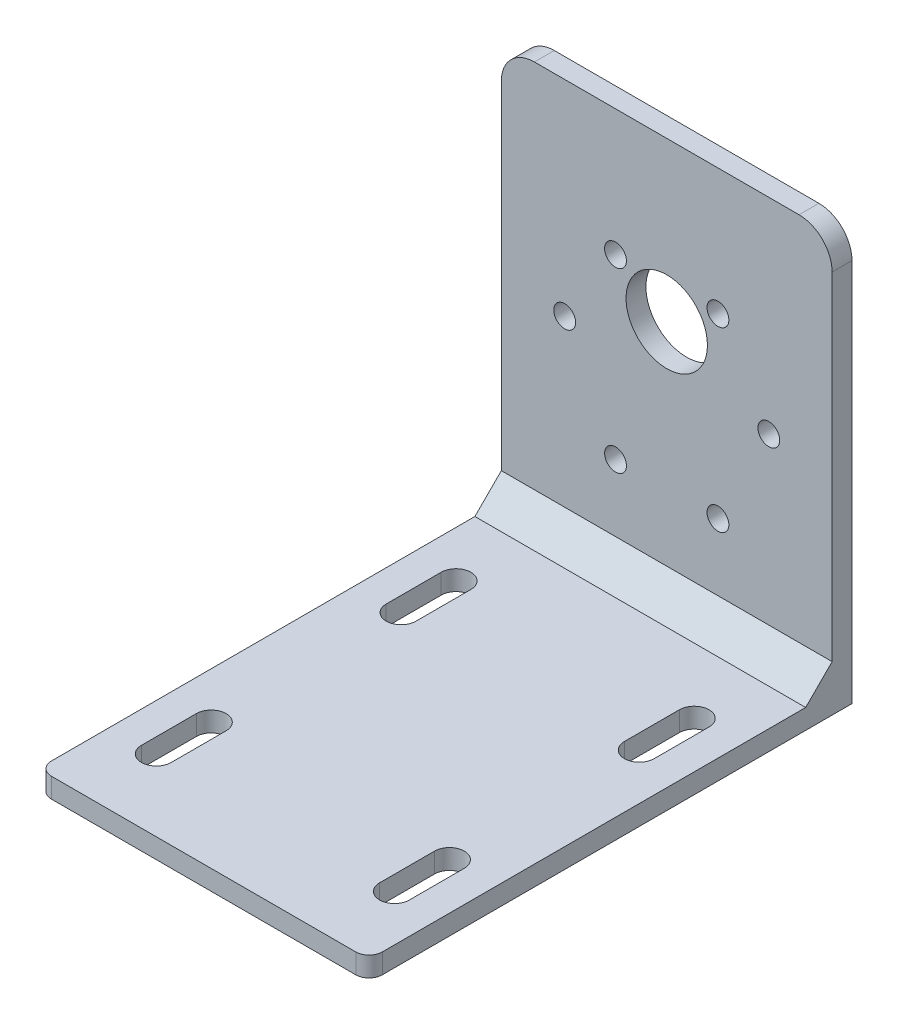
SolidWorks part; units mm, degrees
ref_plane "前视基准面" through (0, 0, 0) normal (0, 0, 1) x (1, 0, 0)
ref_plane "上视基准面" through (0, 0, 0) normal (0, 1, 0) x (1, 0, 0)
ref_plane "右视基准面" through (0, 0, 0) normal (1, 0, 0) x (0, 0, -1)
sketch "草图1" plane through (0, 0, 0) normal (0, 0, 1) x (1, 0, 0)
  line L0 (25, 30) -> (25, 6)
  line L5 (-25, 30) -> (25, 30)
  line L6 (-25, 30) -> (-25, -30)
  line L7 (-25, -30) -> (25, -30)
  line L8 (25, 30) -> (25, -30)
  line L9 (-25, 30) -> (25, -30) construction
  line L10 (-25, -30) -> (25, 30) construction
  line L11 (25, 6) -> (-25, 6)
  line L13 (25, 6) -> (25, -1)
  line L15 (25, -1) -> (15.4272, -1)
  circle A0 centre (0, 6) radius 6.15
  circle A3 centre (0, -2.5) radius 18.5
  circle A4 centre (0, -2.5) radius 15.5
  circle A5 centre (15.4272, -1) radius 1.65
  circle A6 centre (-15.4272, -1) radius 1.65
  circle A7 centre (7.7399, 10.9058) radius 1.65
  circle A8 centre (-7.7399, 10.9058) radius 1.65
  circle A9 centre (-7.7399, -15.9058) radius 1.65
  circle A10 centre (7.7399, -15.9058) radius 1.65
  point P0 (0, 0)
  dimension "D3" = 7
  dimension "D4" = 37
  dimension "D5" = 31
  dimension "D6" = 3.3
  dimension "D8" = 3.3
  dimension "D7" = 12.3
  dimension "D1" = 60
  dimension "D2" = 50
extrude "凸台-拉伸2" add sketch "草图1" along normal blind 3 contours A3 L11 L0 L5 L6 | A3 L11 L6 L7 L8 L15 | A3 L15 L8 L11 | A4 A10 A9 A6 L11 A3 L15 A5 | A4 A8 A7 L11 A3 | A4 A10 A5 L11 A0 A6 A9 | A4 A8 L11 A0 A7 | A5 L15 A3 L11 A4
sketch "草图2" plane through (0, -30, 0) normal (0, -1, 0) x (1, 0, 0)
  line L0 (-25, 0) -> (25, 0)
  line L1 (25, 0) -> (25, 3)
  line L2 (25, 3) -> (-25, 3)
  line L3 (-25, 3) -> (-25, 0)
extrude "凸台-拉伸3" add sketch "草图2" along normal blind 3
sketch "草图3" plane through (0, 0, 3) normal (0, 0, 1) x (1, 0, 0)
  line L0 (25, -33) -> (25, -30)
  line L1 (25, 30) -> (25, -33) construction
  line L2 (25, -30) -> (-25, -30)
  line L3 (-25, 30) -> (-25, -33) construction
  line L4 (-25, -30) -> (-25, -33)
  line L5 (-25, -33) -> (25, -33)
extrude "凸台-拉伸5" add sketch "草图3" along normal blind 70 contours L2 L4 L5 L0
sketch "草图4" plane through (0, -30, 0) normal (0, 1, 0) x (1, 0, 0)
  line L0 (25, -73) -> (25, -21)
  line L1 (25, -73) -> (25, -3) construction
  line L2 (25, -3) -> (25, -6)
  line L3 (25, -73) -> (25, -58)
  line L4 (-25, -38) -> (-18, -38)
  line L5 (-25, -73) -> (-25, -3) construction
  line L6 (25, -58) -> (-18, -58)
  line L7 (-18, -53.85) -> (-18, -62.15) construction
  line L8 (-15.75, -53.85) -> (-15.75, -62.15)
  line L9 (-20.25, -53.85) -> (-20.25, -62.15)
  line L10 (0, -73) -> (0, -3)
  line L11 (25, -73) -> (-25, -73) construction
  line L12 (-25, -3) -> (25, -3) construction
  line L13 (18, -53.85) -> (18, -62.15) construction
  line L14 (15.75, -53.85) -> (15.75, -62.15)
  line L15 (20.25, -53.85) -> (20.25, -62.15)
  line L16 (25, -21) -> (-18, -21)
  line L17 (-18, -16.85) -> (-18, -25.15) construction
  line L18 (-15.75, -16.85) -> (-15.75, -25.15)
  line L19 (-20.25, -16.85) -> (-20.25, -25.15)
  line L20 (18, -16.85) -> (18, -25.15) construction
  line L21 (15.75, -16.85) -> (15.75, -25.15)
  line L22 (20.25, -16.85) -> (20.25, -25.15)
  arc A0 (-15.75, -53.85) -> (-20.25, -53.85) centre (-18, -53.85) ccw
  arc A1 (-20.25, -62.15) -> (-15.75, -62.15) centre (-18, -62.15) ccw
  arc A2 (15.75, -53.85) -> (20.25, -53.85) centre (18, -53.85) cw
  arc A3 (20.25, -62.15) -> (15.75, -62.15) centre (18, -62.15) cw
  arc A4 (-15.75, -16.85) -> (-20.25, -16.85) centre (-18, -16.85) ccw
  arc A5 (-20.25, -25.15) -> (-15.75, -25.15) centre (-18, -25.15) ccw
  arc A6 (15.75, -16.85) -> (20.25, -16.85) centre (18, -16.85) cw
  arc A7 (20.25, -25.15) -> (15.75, -25.15) centre (18, -25.15) cw
  point P16 (-18, -58)
  point P29 (18, -58)
  point P37 (-18, -21)
  point P44 (18, -21)
  dimension "D1" = 3
  dimension "D2" = 15
  dimension "D3" = 15
  dimension "D4" = 4.5
  dimension "D5" = 8.3
  dimension "D6" = 36
  dimension "D7" = 4.5
  dimension "D8" = 8.3
extrude "切除-拉伸1" cut sketch "草图4" against normal through all contours A4 L19 A5 L18 | A6 L22 A7 L21 | A2 L15 A3 L14 | A0 L9 A1 L8
fillet "圆角1" radius 5 2 edges at (-25, 30, 1.5) (25, 30, 1.5)
fillet "圆角2" radius 2 2 edges at (-25, -31.5, 73) (25, -31.5, 73)
sketch "草图5" plane through (0, -30, 0) normal (0, 1, 0) x (1, 0, 0)
  line L0 (25, -3) -> (25, -7)
  line L1 (25, -71) -> (25, -3) construction
  line L2 (25, -7) -> (21, -7)
  line L3 (21, -7) -> (21, -3)
  line L4 (25, -3) -> (-25, -3) construction
  line L5 (21, -3) -> (25, -3)
extrude "凸台-拉伸6" add sketch "草图5" along normal blind 4
sketch "草图6" plane through (21, 0, 0) normal (-1, 0, 0) x (0, 0, 1)
  line L0 (3, -26) -> (7, -26)
  line L1 (7, -26) -> (7, -30)
  line L2 (7, -30) -> (3, -30)
  line L3 (3, -30) -> (3, -26)
extrude "凸台-拉伸7" add sketch "草图6" along normal blind 46
sketch "草图7" plane through (25, 0, 0) normal (1, 0, 0) x (0, 0, -1)
  line L0 (-7, -30) -> (-7, -26)
  line L1 (-7, -26) -> (-3, -26)
  line L2 (-3, -26) -> (-7, -30)
extrude "切除-拉伸2" cut sketch "草图7" against normal through all
